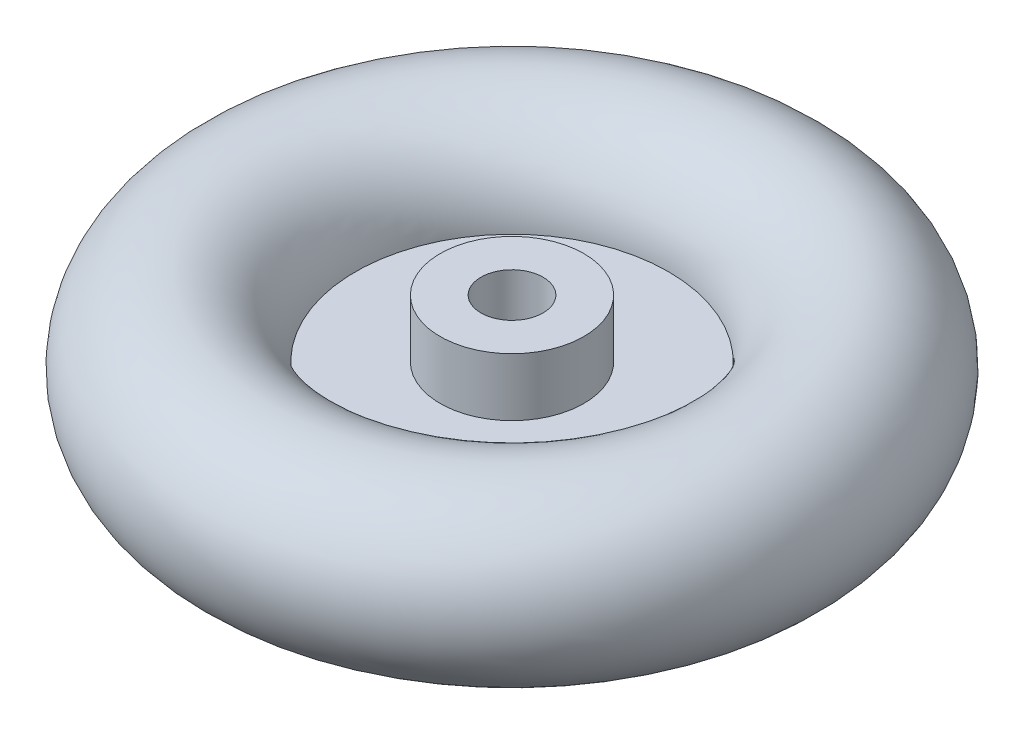
SolidWorks part; units mm, degrees
ref_plane "前视基准面" through (0, 0, 0) normal (0, 0, 1) x (1, 0, 0)
ref_plane "上视基准面" through (0, 0, 0) normal (0, 1, 0) x (1, 0, 0)
ref_plane "右视基准面" through (0, 0, 0) normal (1, 0, 0) x (0, 0, -1)
sketch "草图1" plane through (0, 0, 0) normal (0, 0, 1) x (1, 0, 0)
  line L0 (-6.3802, 0.5391) -> (-6.3802, 75.519) construction
  line L9 (105, 0.0775) -> (105, 0)
  line L11 (15.6198, 46) -> (15.6198, 28.2495)
  line L12 (15.6198, 28.2495) -> (41.515, 28.2495)
  line L18 (41.515, 25.5974) -> (15.6198, 25.5974)
  line L19 (15.6198, 25.5974) -> (15.6198, 0)
  line L21 (41.515, 28.2495) -> (41.515, 51.2695) construction
  line L22 (41.515, 51.2695) -> (94.515, 51.2695) construction
  line L23 (94.515, 51.2695) -> (94.515, -1.7305) construction
  line L24 (94.515, -1.7305) -> (41.515, -1.7305) construction
  line L25 (41.515, -1.7305) -> (41.515, 25.5974) construction
  line L26 (15.6198, 46) -> (3.1198, 46)
  line L27 (3.1198, 46) -> (3.1198, 0)
  line L28 (3.1198, 0) -> (15.6198, 0)
  arc A0 (41.515, 28.2495) -> (41.515, 25.5974) centre (67.9984, 26.9234) cw
  dimension "D4" = 44
  dimension "D1" = 19
  dimension "D2" = 46
  dimension "D3" = 53
revolve "旋转2" add sketch "草图1" angle 360 about L0
